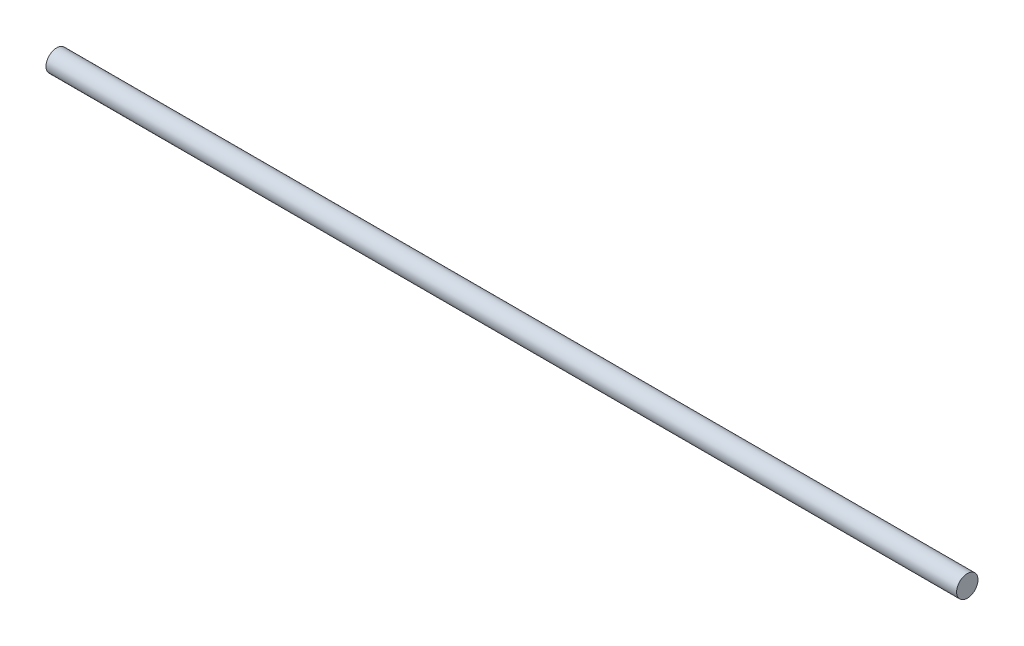
SolidWorks part; units mm, degrees
ref_plane "Front" through (0, 0, 0) normal (0, 0, 1) x (1, 0, 0)
ref_plane "Top" through (0, 0, 0) normal (0, 1, 0) x (1, 0, 0)
ref_plane "Right" through (0, 0, 0) normal (1, 0, 0) x (0, 0, -1)
sketch "Sketch1" plane through (0, 0, 0) normal (1, 0, 0) x (0, 0, -1)
  circle A0 centre (0, 0) radius 17.907
  dimension "D1" = 35.814
extrude "Boss-Extrude1" add sketch "Sketch1" along normal mid plane 1524
